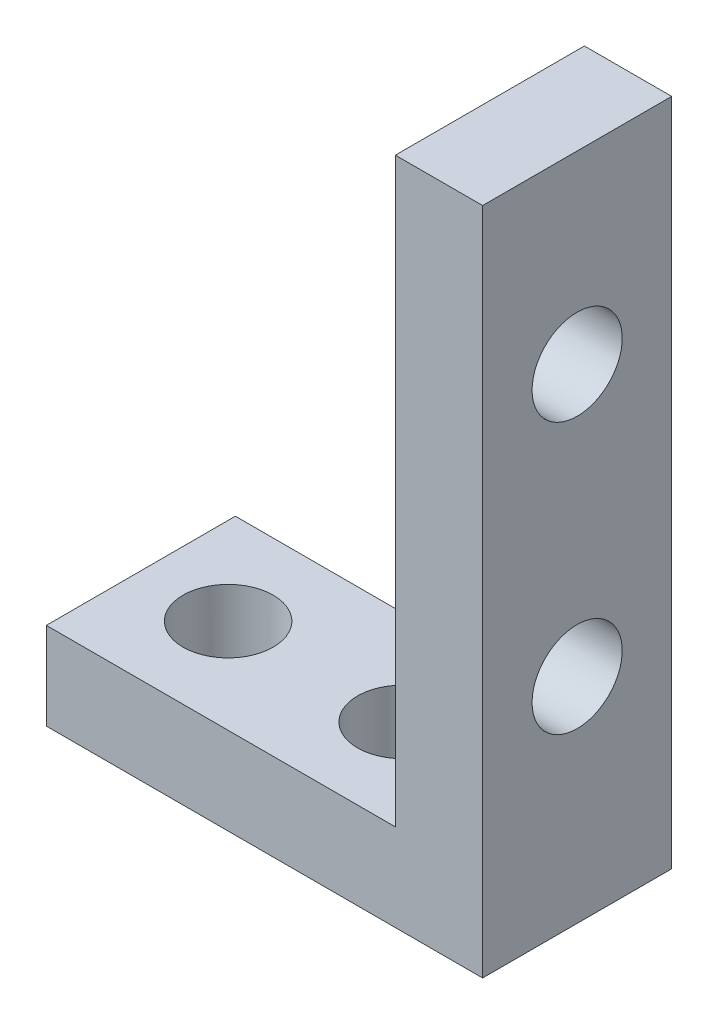
SolidWorks part; units mm, degrees
ref_plane "정면" through (0, 0, 0) normal (0, 0, 1) x (1, 0, 0)
ref_plane "윗면" through (0, 0, 0) normal (0, 1, 0) x (1, 0, 0)
ref_plane "우측면" through (0, 0, 0) normal (1, 0, 0) x (0, 0, -1)
sketch "Sketch1" plane through (0, 0, 0) normal (0, 0, 1) x (1, 0, 0)
  line L1 (-21.3619, -2.625) -> (-9.3619, -2.625)
  line L2 (-21.3619, -2.625) -> (-21.3619, -5.625)
  line L3 (-21.3619, -5.625) -> (-9.3619, -5.625)
  line L5 (-9.3619, -5.625) -> (-6.3619, -5.625)
  line L6 (-9.3619, -2.625) -> (-9.3619, 17.375)
  line L7 (-9.3619, 17.375) -> (-6.3619, 17.375)
  line L8 (-6.3619, -5.625) -> (-6.3619, 17.375)
  dimension "D1" = 23
  dimension "D2" = 12
  dimension "D3" = 3
  dimension "D4" = 3
extrude "Boss-Extrude1" add sketch "Sketch1" along normal blind 6.5
sketch "Sketch2" plane through (0, -2.625, 0) normal (0, 1, 0) x (1, 0, 0)
  line L0 (-21.3619, -3.25) -> (-9.3619, -3.25) construction
  line L1 (-21.3619, -6.5) -> (-21.3619, 0) construction
  line L2 (-9.3619, -6.5) -> (-9.3619, 0) construction
  line L3 (-15.3619, 0) -> (-15.3619, -6.5) construction
  line L4 (-9.3619, 0) -> (-21.3619, 0) construction
  line L5 (-9.3619, -6.5) -> (-21.3619, -6.5) construction
  circle A0 centre (-12.3619, -3.25) radius 1.55
  circle A1 centre (-18.3619, -3.25) radius 1.55
  dimension "D1" = 3.1
  dimension "D2" = 3
extrude "Cut-Extrude1" cut sketch "Sketch2" against normal blind 10 contours A0 | A1
sketch "Sketch3" plane through (-9.3619, 0, 0) normal (-1, 0, 0) x (0, 0, 1)
  line L0 (3.25, 17.375) -> (3.25, -2.625) construction
  line L1 (6.5, 17.375) -> (0, 17.375) construction
  line L2 (6.5, -2.625) -> (0, -2.625) construction
  circle A0 centre (3.25, 1.725) radius 1.55
  circle A1 centre (3.25, 11.025) radius 1.55
  dimension "D1" = 3.1
  dimension "D2" = 3.1
  dimension "D3" = 9.3
  dimension "D4" = 4.35
extrude "Cut-Extrude2" cut sketch "Sketch3" against normal blind 10
